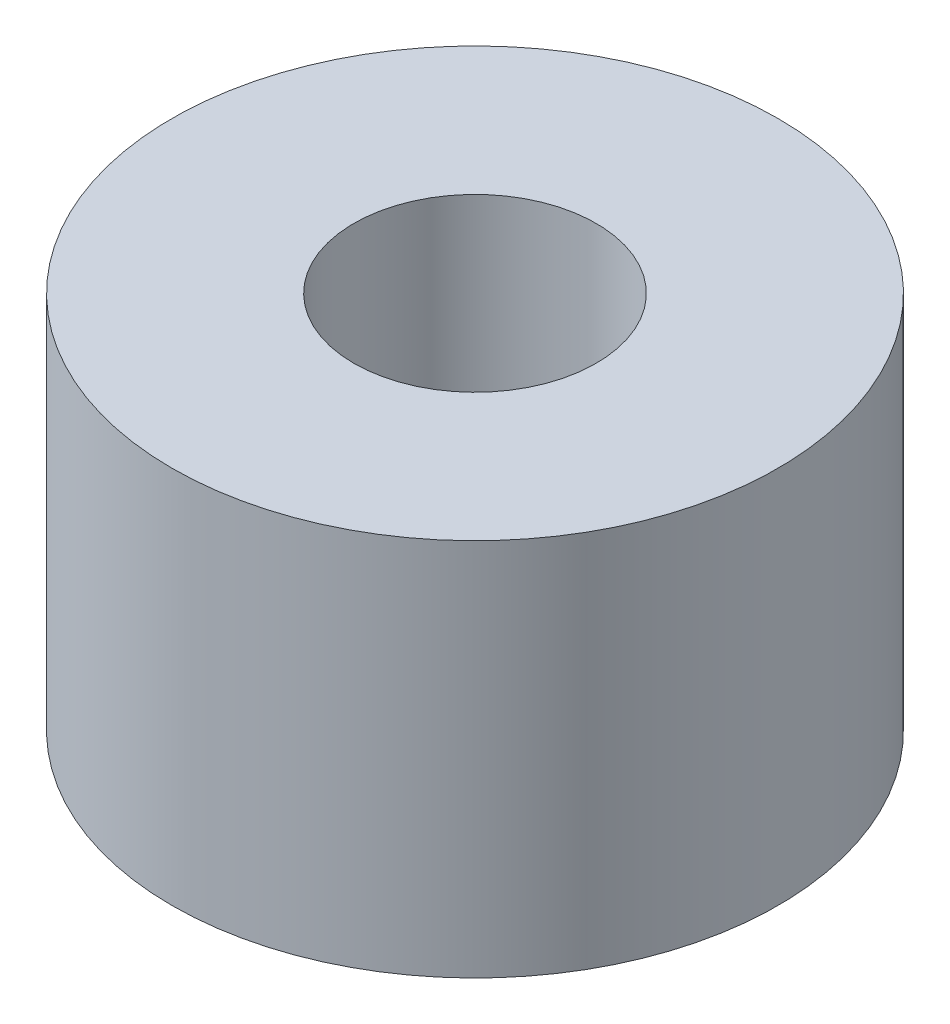
SolidWorks part; units mm, degrees
ref_plane "前视基准面" through (0, 0, 0) normal (0, 0, 1) x (1, 0, 0)
ref_plane "上视基准面" through (0, 0, 0) normal (0, 1, 0) x (1, 0, 0)
ref_plane "右视基准面" through (0, 0, 0) normal (1, 0, 0) x (0, 0, -1)
sketch "草图1" plane through (0, 0, 0) normal (0, 1, 0) x (1, 0, 0)
  circle A0 centre (0, 0) radius 4
  circle A1 centre (0, 0) radius 1.6
  dimension "D1" = 3.2
  dimension "D2" = 8
extrude "凸台-拉伸1" add sketch "草图1" along normal blind 5
